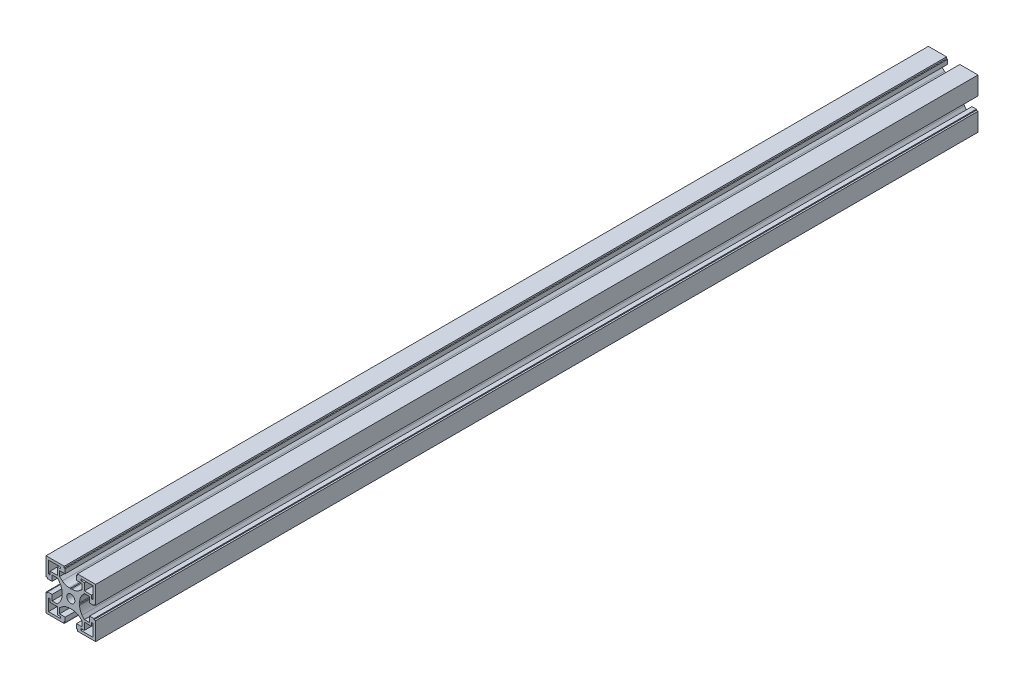
SolidWorks part; units mm, degrees
ref_plane "Front Plane" through (0, 0, 0) normal (0, 0, 1) x (1, 0, 0)
ref_plane "Top Plane" through (0, 0, 0) normal (0, 1, 0) x (1, 0, 0)
ref_plane "Right Plane" through (0, 0, 0) normal (1, 0, 0) x (0, 0, -1)
sketch "Model" plane through (0, 0, 0) normal (0, 0, 1) x (1, 0, 0)
  line L0 (20.25, -9.25) -> (20.25, -20.25)
  line L1 (20.25, -9.25) -> (18.75, -9.25)
  line L2 (18.75, -9.25) -> (18.75, -12.25)
  line L3 (18.75, -12.25) -> (12.25, -12.25)
  line L4 (12.25, -12.25) -> (12.25, -18.75)
  line L5 (12.25, -18.75) -> (9.25, -18.75)
  line L6 (9.25, -18.75) -> (9.25, -20.25)
  line L7 (20.25, -20.25) -> (9.25, -20.25)
  line L8 (9.25, 20.25) -> (20.25, 20.25)
  line L9 (9.25, 20.25) -> (9.25, 18.75)
  line L10 (9.25, 18.75) -> (12.25, 18.75)
  line L11 (12.25, 18.75) -> (12.25, 12.25)
  line L12 (12.25, 12.25) -> (18.75, 12.25)
  line L13 (18.75, 12.25) -> (18.75, 9.25)
  line L14 (18.75, 9.25) -> (20.25, 9.25)
  line L15 (20.25, 20.25) -> (20.25, 9.25)
  line L16 (-9.25, -20.25) -> (-20.25, -20.25)
  line L17 (-9.25, -20.25) -> (-9.25, -18.75)
  line L18 (-9.25, -18.75) -> (-12.25, -18.75)
  line L19 (-12.25, -18.75) -> (-12.25, -12.25)
  line L20 (-12.25, -12.25) -> (-18.75, -12.25)
  line L21 (-18.75, -12.25) -> (-18.75, -9.25)
  line L22 (-18.75, -9.25) -> (-20.25, -9.25)
  line L23 (-20.25, -20.25) -> (-20.25, -9.25)
  line L24 (-20.25, 20.25) -> (-9.25, 20.25)
  line L25 (-20.25, 9.25) -> (-20.25, 20.25)
  line L26 (-20.25, 9.25) -> (-18.75, 9.25)
  line L27 (-18.75, 9.25) -> (-18.75, 12.25)
  line L28 (-18.75, 12.25) -> (-12.25, 12.25)
  line L29 (-12.25, 12.25) -> (-12.25, 18.75)
  line L30 (-12.25, 18.75) -> (-9.25, 18.75)
  line L31 (-9.25, 18.75) -> (-9.25, 20.25)
  line L32 (0.5, 8) -> (1.4727, 8)
  line L33 (7.7467, 10.213) -> (10.25, 12.2299)
  line L34 (10.25, 12.2299) -> (10.25, 17)
  line L35 (10.25, 17) -> (5.1, 17)
  line L36 (5.1, 17) -> (5.1, 21)
  line L37 (5.1, 21) -> (6, 21)
  line L38 (6, 22.5) -> (6, 21)
  line L39 (22.5, 22.5) -> (6, 22.5)
  line L40 (22.5, 6) -> (22.5, 22.5)
  line L41 (22.5, 6) -> (21, 6)
  line L42 (21, 6) -> (21, 5.1)
  line L43 (21, 5.1) -> (17, 5.1)
  line L44 (17, 5.1) -> (17, 10.25)
  line L45 (17, 10.25) -> (12.2299, 10.25)
  line L46 (12.2299, 10.25) -> (10.213, 7.7467)
  line L47 (8, 1.4727) -> (8, 0.5)
  line L48 (8, 0.5) -> (7.5, 0)
  line L49 (7.5, 0) -> (8, -0.5)
  line L50 (8, -0.5) -> (8, -1.4727)
  line L51 (10.213, -7.7467) -> (12.2299, -10.25)
  line L52 (12.2299, -10.25) -> (17, -10.25)
  line L53 (17, -10.25) -> (17, -5.1)
  line L54 (17, -5.1) -> (21, -5.1)
  line L55 (21, -5.1) -> (21, -6)
  line L56 (22.5, -6) -> (21, -6)
  line L57 (22.5, -22.5) -> (22.5, -6)
  line L58 (6, -22.5) -> (22.5, -22.5)
  line L59 (6, -22.5) -> (6, -21)
  line L60 (6, -21) -> (5.1, -21)
  line L61 (5.1, -21) -> (5.1, -17)
  line L62 (5.1, -17) -> (10.25, -17)
  line L63 (10.25, -17) -> (10.25, -12.2299)
  line L64 (10.25, -12.2299) -> (7.7467, -10.213)
  line L65 (1.4727, -8) -> (0.5, -8)
  line L66 (0.5, -8) -> (0, -7.5)
  line L67 (0, -7.5) -> (-0.5, -8)
  line L68 (-0.5, -8) -> (-1.4727, -8)
  line L69 (-7.7467, -10.213) -> (-10.25, -12.2299)
  line L70 (-10.25, -12.2299) -> (-10.25, -17)
  line L71 (-10.25, -17) -> (-5.1, -17)
  line L72 (-5.1, -17) -> (-5.1, -21)
  line L73 (-5.1, -21) -> (-6, -21)
  line L74 (-6, -22.5) -> (-6, -21)
  line L75 (-22.5, -22.5) -> (-6, -22.5)
  line L76 (-22.5, -6) -> (-22.5, -22.5)
  line L77 (-22.5, -6) -> (-21, -6)
  line L78 (-21, -6) -> (-21, -5.1)
  line L79 (-21, -5.1) -> (-17, -5.1)
  line L80 (-17, -5.1) -> (-17, -10.25)
  line L81 (-17, -10.25) -> (-12.2299, -10.25)
  line L82 (-12.2299, -10.25) -> (-10.213, -7.7467)
  line L83 (-8, -1.4727) -> (-8, -0.5)
  line L84 (-8, -0.5) -> (-7.5, 0)
  line L85 (-7.5, 0) -> (-8, 0.5)
  line L86 (-8, 0.5) -> (-8, 1.4727)
  line L87 (-10.213, 7.7467) -> (-12.2299, 10.25)
  line L88 (-12.2299, 10.25) -> (-17, 10.25)
  line L89 (-17, 10.25) -> (-17, 5.1)
  line L90 (-17, 5.1) -> (-21, 5.1)
  line L91 (-21, 5.1) -> (-21, 6)
  line L92 (-22.5, 6) -> (-21, 6)
  line L93 (-22.5, 22.5) -> (-22.5, 6)
  line L94 (-6, 22.5) -> (-22.5, 22.5)
  line L95 (-6, 22.5) -> (-6, 21)
  line L96 (-6, 21) -> (-5.1, 21)
  line L97 (-5.1, 21) -> (-5.1, 17)
  line L98 (-5.1, 17) -> (-10.25, 17)
  line L99 (-10.25, 17) -> (-10.25, 12.2299)
  line L100 (-10.25, 12.2299) -> (-7.7467, 10.213)
  line L101 (-1.4727, 8) -> (-0.5, 8)
  line L102 (-0.5, 8) -> (0, 7.5)
  line L103 (0, 7.5) -> (0.5, 8)
  arc A0 (1.4727, 8) -> (7.7467, 10.213) centre (1.4727, 18) ccw
  arc A1 (10.213, 7.7467) -> (8, 1.4727) centre (18, 1.4727) ccw
  arc A2 (8, -1.4727) -> (10.213, -7.7467) centre (18, -1.4727) ccw
  arc A3 (7.7467, -10.213) -> (1.4727, -8) centre (1.4727, -18) ccw
  arc A4 (-1.4727, -8) -> (-7.7467, -10.213) centre (-1.4727, -18) ccw
  arc A5 (-10.213, -7.7467) -> (-8, -1.4727) centre (-18, -1.4727) ccw
  arc A6 (-7.7467, 10.213) -> (-1.4727, 8) centre (-1.4727, 18) ccw
  circle A7 centre (0, 0) radius 3.7
  arc A8 (-8, 1.4727) -> (-10.213, 7.7467) centre (-18, 1.4727) ccw
  dimension "Vijak_diametar" = 7.4
extrude "Boss-Extrude1" add sketch "Model" against normal blind 800
equation "\"Lx_Alu_Profile_45x45H_Tuli\"= 800"
equation "\"LX_extrude2@Boss-Extrude1\"=\"Lx_Alu_Profile_45x45H_Tuli\""
